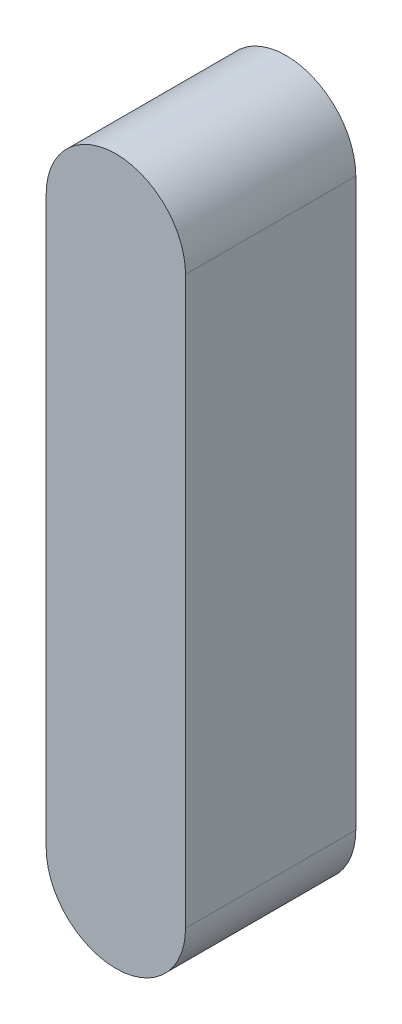
SolidWorks part; units mm, degrees
ref_plane "Front Plane" through (0, 0, 0) normal (0, 0, 1) x (1, 0, 0)
ref_plane "Top Plane" through (0, 0, 0) normal (0, 1, 0) x (1, 0, 0)
ref_plane "Right Plane" through (0, 0, 0) normal (1, 0, 0) x (0, 0, -1)
sketch "Stem Block Sketch" plane through (0, 0, 0) normal (0, 0, 1) x (1, 0, 0)
  line L0 (0, 0) -> (0, 365.7967) construction
  line L1 (-45, 0) -> (-45, 365.7967)
  line L2 (45, 0) -> (45, 365.7967)
  arc A0 (-45, 0) -> (45, 0) centre (0, 0) ccw
  arc A1 (45, 365.7967) -> (-45, 365.7967) centre (0, 365.7967) ccw
  point P3 (0, 182.8984)
  dimension "D1" = 90
extrude "Stem Block Extrude" add sketch "Stem Block Sketch" along normal up to surface (55 mm away) and the other way up to surface (55 mm away)
equation "\"D1@Stem Block Sketch\" = \"D1@Stem Block Sketch@Gripper Segment 01<1>.Part\""
